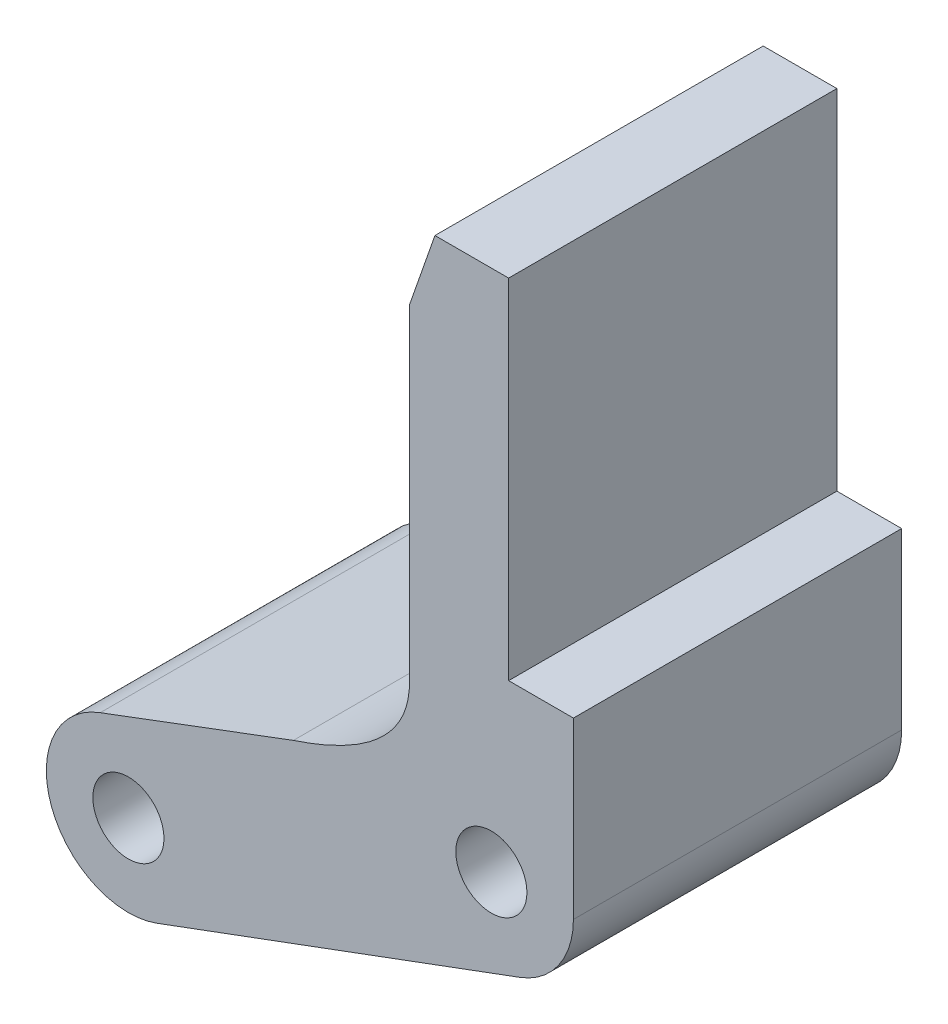
SolidWorks part; units mm, degrees
material "ABS"
ref_plane "Plan de face" through (0, 0, 0) normal (0, 0, 1) x (1, 0, 0)
ref_plane "Plan de dessus" through (0, 0, 0) normal (0, 1, 0) x (1, 0, 0)
ref_plane "Plan de droite" through (0, 0, 0) normal (1, 0, 0) x (0, 0, -1)
sketch "Esquisse1" plane through (0, 0, 0) normal (0, 0, 1) x (1, 0, 0)
  line L0 (149.5318, 51.5092) -> (223.8317, 51.3982) construction
  line L1 (158.766, 185.6233) -> (159.7017, 188.2967)
  line L2 (159.7017, 188.2967) -> (162.396, 188.2967)
  line L4 (164.7643, 175.5506) -> (162.396, 175.5506)
  line L5 (162.396, 175.5506) -> (162.396, 188.2967)
  line L7 (158.766, 185.6233) -> (158.766, 173.8392)
  line L8 (164.7643, 175.5506) -> (164.7643, 169.1747)
  line L9 (148.4952, 164.2539) -> (161.7643, 169.1747) construction
  line L10 (147.4661, 167.0718) -> (155.5501, 170.1099)
  line L11 (149.5243, 161.4359) -> (162.7934, 166.3567)
  arc A0 (147.4661, 167.0718) -> (149.5243, 161.4359) centre (148.4952, 164.2539) ccw
  arc A1 (162.7934, 166.3567) -> (164.7643, 169.1747) centre (161.7643, 169.1747) ccw
  circle A2 centre (148.4952, 164.2539) radius 1.3
  circle A3 centre (161.7643, 169.1747) radius 1.3
  spline S0 degree 2 poles (158.766, 173.8392) (158.908, 171.1625) (154.5287, 169.7261) knots 0 0 0 1 1 1
  point P14 (157.2657, 167.4691)
  dimension "D2" = 2.6
  dimension "D3" = 3
  dimension "D1" = 2.6
extrude "Boss.-Extru.1" add sketch "Esquisse1" along normal blind 12
